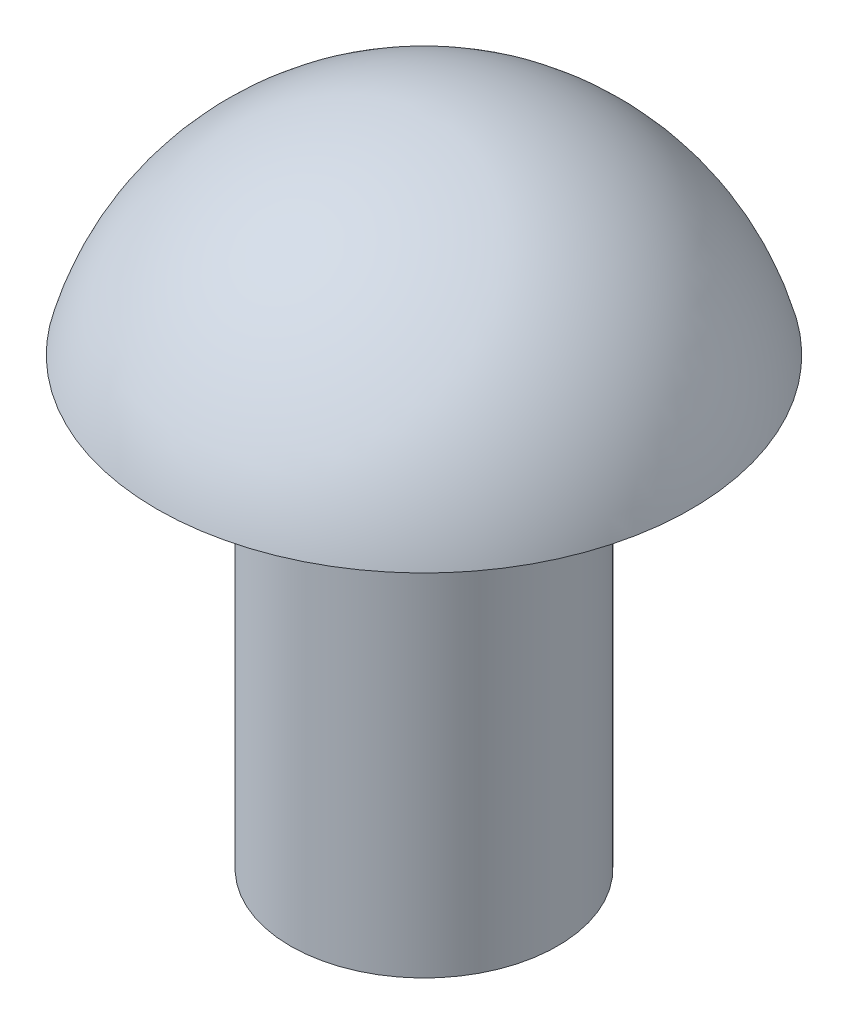
SolidWorks part; units mm, degrees
ref_plane "Front Plane" through (0, 0, 0) normal (0, 0, 1) x (1, 0, 0)
ref_plane "Top Plane" through (0, 0, 0) normal (0, 1, 0) x (1, 0, 0)
ref_plane "Right Plane" through (0, 0, 0) normal (1, 0, 0) x (0, 0, -1)
sketch "Sketch1" plane through (0, 0, 0) normal (0, 1, 0) x (1, 0, 0)
  circle A0 centre (0, 0) radius 76.2
  dimension "D1" = 152.4
extrude "Boss-Extrude1" add sketch "Sketch1" along normal blind 254
sketch "Sketch2" plane through (0, 0, 0) normal (1, 0, 0) x (0, 0, -1)
  line L0 (0, 254) -> (0, 371.362) construction
  line L1 (76.2, 254) -> (-76.2, 254) construction
  line L2 (76.2, 254) -> (152.4, 254)
  line L3 (-76.2, 254) -> (-152.4, 254)
  line L4 (76.2, 254) -> (-76.2, 254)
  line L5 (-76.2, 254) -> (76.2, 254)
  arc A0 (-152.4, 254) -> (152.4, 254) centre (0, 213.7318) cw
  dimension "D1" = 76.2
revolve "Revolve3" add sketch "Sketch2" angle 360 about L0
scale "Scale1" scale about centroid uniform scaling yes scale factor 0.03937
